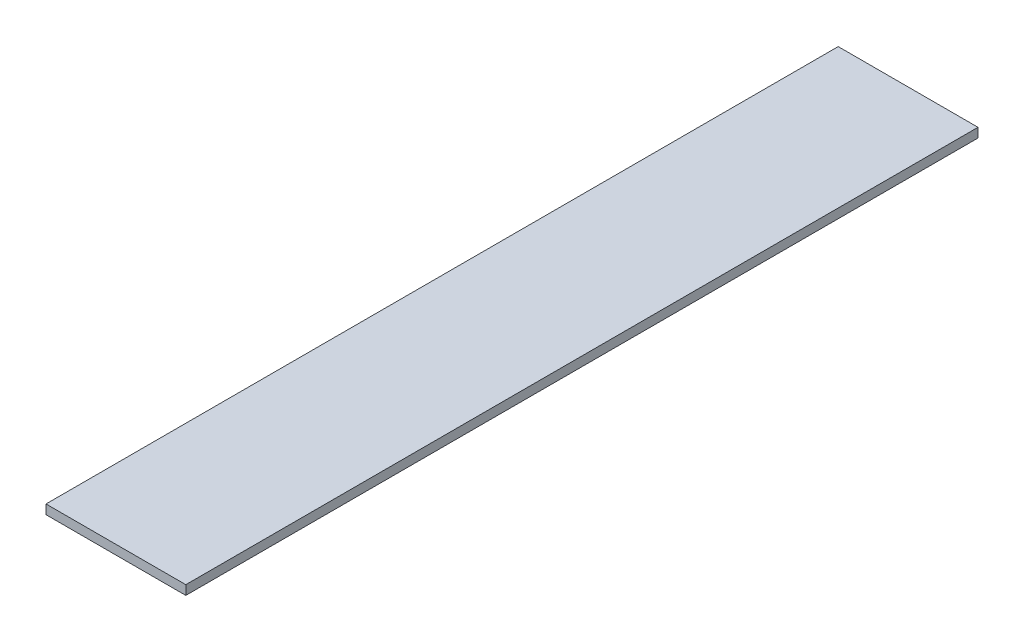
SolidWorks part; units mm, degrees
ref_plane "Front" through (0, 0, 0) normal (0, 0, 1) x (1, 0, 0)
ref_plane "Top" through (0, 0, 0) normal (0, 1, 0) x (1, 0, 0)
ref_plane "Right" through (0, 0, 0) normal (1, 0, 0) x (0, 0, -1)
sketch "Sketch1" plane through (0, 0, 0) normal (0, 1, 0) x (1, 0, 0)
  line L1 (0, 0) -> (15, 0)
  line L2 (0, 0) -> (0, 85)
  line L3 (0, 85) -> (15, 85)
  line L4 (15, 0) -> (15, 85)
  dimension "D1" = 85
  dimension "D2" = 15
extrude "Boss-Extrude1" add sketch "Sketch1" along normal blind 1
